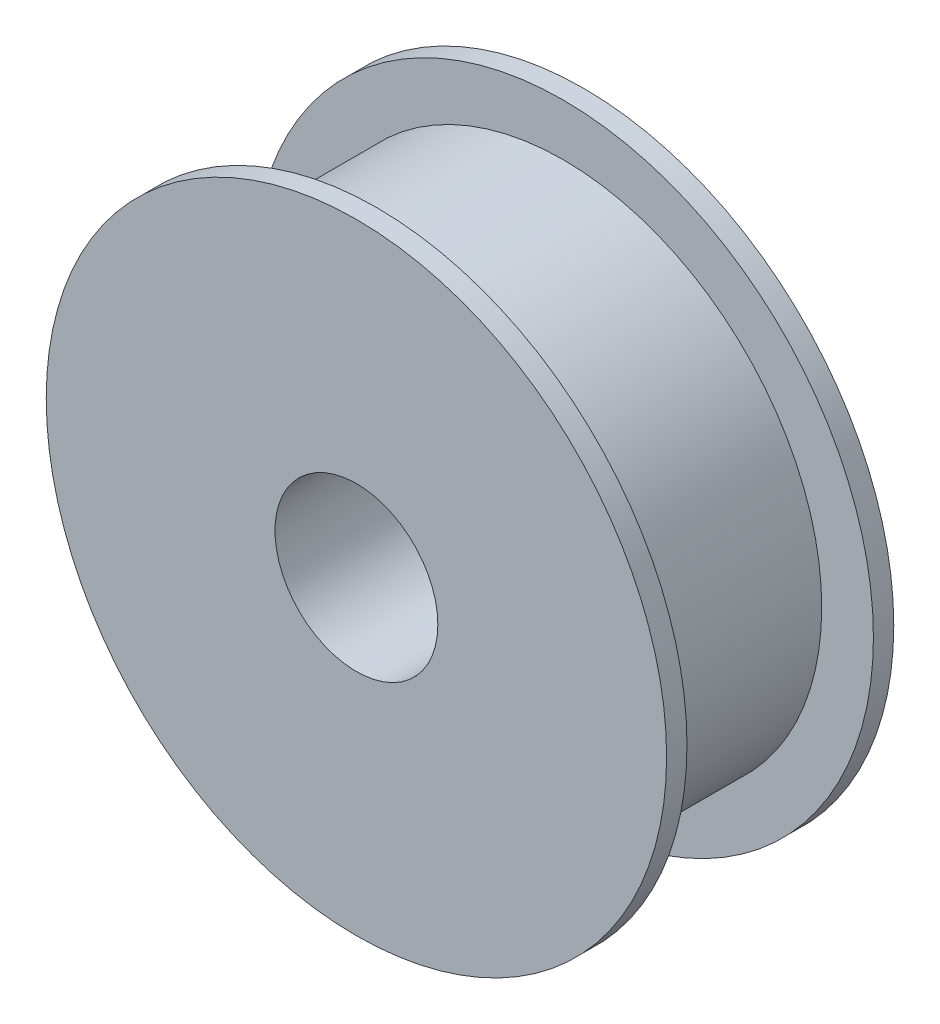
SolidWorks part; units mm, degrees
ref_plane "Front Plane" through (0, 0, 0) normal (0, 0, 1) x (1, 0, 0)
ref_plane "Top Plane" through (0, 0, 0) normal (0, 1, 0) x (1, 0, 0)
ref_plane "Right Plane" through (0, 0, 0) normal (1, 0, 0) x (0, 0, -1)
sketch "Sketch1" plane through (0, 0, 0) normal (0, 0, 1) x (1, 0, 0)
  circle A0 centre (0, 0) radius 63.5
  circle A1 centre (0, 0) radius 20
extrude "Boss-Extrude1" add sketch "Sketch1" along normal blind 50.8
sketch "Sketch3" plane through (0, 0, 0) normal (0, 0, 1) x (1, 0, 0)
  circle A0 centre (0, 0) radius 76.2
  circle A2 centre (0, 0) radius 5.1
  circle A3 centre (0, 8) radius 1.5
  circle A4 centre (8, 0) radius 1.5
  circle A5 centre (0, -8) radius 1.5
  circle A6 centre (-8, 0) radius 1.5
  dimension "D1" = 4
extrude "Boss-Extrude2" add sketch "Sketch3" along normal blind 5
sketch "Sketch4" plane through (0, 0, 50.8) normal (0, 0, 1) x (1, 0, 0)
  circle A0 centre (0, 0) radius 76.2
  circle A1 centre (0, 0) radius 20
extrude "Boss-Extrude3" add sketch "Sketch4" along normal blind 5
sketch "Sketch5" plane through (0, 0, 0) normal (0, 0, -1) x (-1, 0, 0)
  circle A0 centre (0, 0) radius 11.1
extrude "Cut-Extrude1" cut sketch "Sketch5" against normal blind 1.2
sketch "Sketch6" plane through (0, 0, 0) normal (0, 1, 0) x (1, 0, 0)
  line L0 (-59.6633, -29.8844) -> (-59.6633, -24.3281)
  line L1 (-59.6633, -29.8844) -> (-67.3367, -29.8844)
  line L2 (-59.6633, -24.3281) -> (-67.3367, -24.3281)
  arc A0 (-67.3367, -24.3281) -> (-67.3367, -29.8844) centre (-67.3367, -27.1062) ccw
  circle A1 centre (-67.3367, -27.1062) radius 1.5875
  point P1 (-63.5, -27.9)
extrude "Boss-Extrude4" add sketch "Sketch6" along normal mid plane 5
